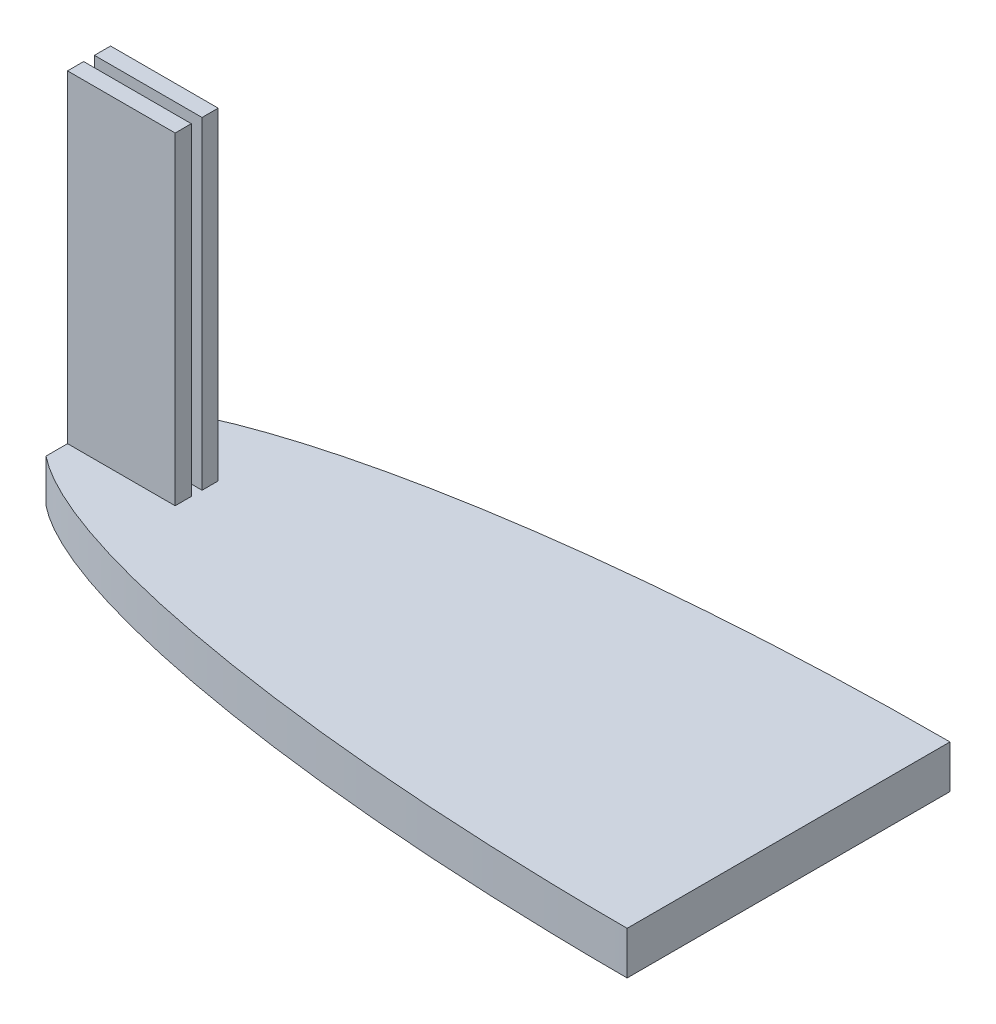
SolidWorks part; units mm, degrees
ref_plane "Front Plane" through (0, 0, 0) normal (0, 0, 1) x (1, 0, 0)
ref_plane "Top Plane" through (0, 0, 0) normal (0, 1, 0) x (1, 0, 0)
ref_plane "Right Plane" through (0, 0, 0) normal (1, 0, 0) x (0, 0, -1)
sketch "Sketch1" plane through (0, 0, 0) normal (0, 1, 0) x (1, 0, 0)
  line L0 (-32.5, -15) -> (32.5, 15) construction
  line L1 (32.5, -15) -> (-32.5, -15) construction
  line L2 (32.5, -15) -> (32.5, 15)
  line L3 (32.5, 15) -> (-32.5, 15) construction
  line L4 (-32.5, -15) -> (-32.5, 15) construction
  line L5 (32.5, -15) -> (32.5, 15)
  line L6 (-32.5, 4) -> (-32.5, -4)
  ellipse E0 centre (32.5, 0) end of major axis (99.9422, 0) minor radius 15 (-32.5, -4) -> (32.5, -15) ccw
  ellipse E1 centre (32.5, 0) end of major axis (99.9422, 0) minor radius 15 (32.5, 15) -> (-32.5, 4) ccw
  point P5 (0, 0)
  point P6 (-45.9143, 0)
  point P18 (-37.1288, 0)
  dimension "D1" = 30
  dimension "D2" = 65
  dimension "D3" = 8
extrude "Boss-Extrude1" add sketch "Sketch1" along normal blind 4 contours L2 E1 L6 E0
sketch "Sketch2" plane through (0, 4, 0) normal (0, 1, 0) x (1, 0, 0)
  line L0 (0, 0) -> (-32.5, 0) construction
  line L1 (-32.5, -2) -> (-22.5, -2)
  line L3 (-32.5, 2) -> (-22.5, 2)
  line L5 (-22.5, -2) -> (-22.5, -0.5)
  line L6 (-22.5, 0.5) -> (-22.5, 2)
  line L8 (-32.5, -0.5) -> (-22.5, -0.5)
  line L9 (-32.5, 0.5) -> (-22.5, 0.5)
  line L10 (-32.5, 0.5) -> (-32.5, 2)
  line L11 (-32.5, -0.5) -> (-32.5, -2)
  line L12 (-22.5, -0.5) -> (-22.5, 0.5) construction
  line L13 (-32.5, 4) -> (-32.5, -4) construction
  point P0 (-32.5, 0)
  point P8 (-32.5, 0)
  point P14 (-22.5, 0)
  point P15 (-60.4763, 0)
  dimension "D1" = 10
  dimension "D2" = 4
  dimension "D3" = 1
extrude "Boss-Extrude3" add sketch "Sketch2" along normal blind 30
